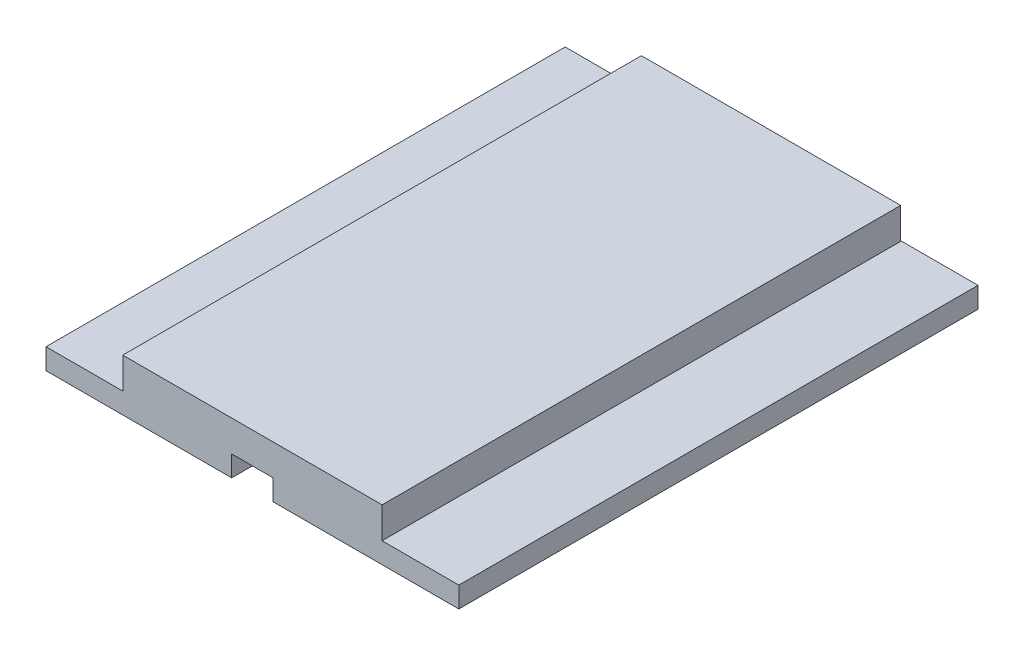
SolidWorks part; units mm, degrees
ref_plane "Front Plane" through (0, 0, 0) normal (0, 0, 1) x (1, 0, 0)
ref_plane "Top Plane" through (0, 0, 0) normal (0, 1, 0) x (1, 0, 0)
ref_plane "Right Plane" through (0, 0, 0) normal (1, 0, 0) x (0, 0, -1)
sketch "Sketch1" plane through (0, 0, 0) normal (0, 1, 0) x (1, 0, 0)
  line L1 (-1.943, 8.8472) -> (3.057, 8.8472)
  line L2 (-1.943, 8.8472) -> (-1.943, -1.1528)
  line L3 (-1.943, -1.1528) -> (3.057, -1.1528)
  line L4 (3.057, 8.8472) -> (3.057, -1.1528)
  dimension "D1" = 5
  dimension "D2" = 10
extrude "Boss-Extrude1" add sketch "Sketch1" along normal blind 0.6
sketch "Sketch2" plane through (0, 0, 0) normal (0, -1, 0) x (1, 0, 0)
  line L0 (-1.943, 1.1528) -> (3.057, 1.1528) construction
  line L1 (0.957, 1.1528) -> (4.557, 1.1528)
  line L2 (0.957, 1.1528) -> (0.957, -8.8576)
  line L3 (0.957, -8.8576) -> (4.557, -8.8576)
  line L4 (4.557, 1.1528) -> (4.557, -8.8576)
  line L5 (3.057, 1.1528) -> (3.057, -8.8472) construction
  line L6 (0.157, 1.1528) -> (-3.443, 1.1528)
  line L7 (0.157, 1.1528) -> (0.157, -8.8576)
  line L8 (0.157, -8.8576) -> (-3.443, -8.8576)
  line L9 (-3.443, 1.1528) -> (-3.443, -8.8576)
  dimension "D1" = 0.8
  dimension "D2" = 3.6
  dimension "D3" = 3.6
  dimension "D4" = 2.1
extrude "Boss-Extrude2" add sketch "Sketch2" along normal blind 0.4
sketch "Sketch4" plane through (4.557, 0, 0) normal (1, 0, 0) x (0, 0, -1)
  line L1 (-1.1528, 0) -> (8.8576, 0)
  line L2 (-1.1528, 0) -> (-1.1528, -0.4)
  line L3 (-1.1528, -0.4) -> (8.8576, -0.4)
  line L4 (8.8576, 0) -> (8.8576, -0.4)
extrude "Cut-Extrude2" cut sketch "Sketch4" against normal blind 0.02
sketch "Sketch5" plane through (-3.443, 0, 0) normal (-1, 0, 0) x (0, 0, 1)
  line L1 (-8.8576, 0) -> (1.1528, 0)
  line L2 (-8.8576, 0) -> (-8.8576, -0.4)
  line L3 (-8.8576, -0.4) -> (1.1528, -0.4)
  line L4 (1.1528, 0) -> (1.1528, -0.4)
extrude "Cut-Extrude3" cut sketch "Sketch5" against normal blind 0.02
